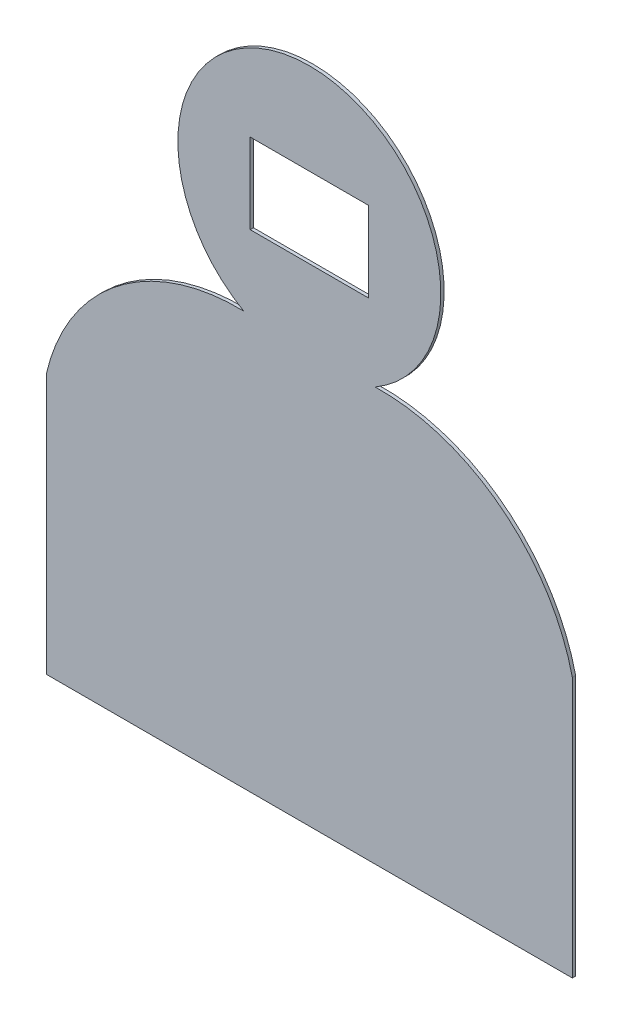
SolidWorks part; units mm, degrees
ref_plane "Front Plane" through (0, 0, 0) normal (0, 0, 1) x (1, 0, 0)
ref_plane "Top Plane" through (0, 0, 0) normal (0, 1, 0) x (1, 0, 0)
ref_plane "Right Plane" through (0, 0, 0) normal (1, 0, 0) x (0, 0, -1)
sketch "Sketch1" plane through (0, 0, 0) normal (0, 0, 1) x (1, 0, 0)
  line L2 (-447.5916, 337.0425) -> (-447.5916, -59.0825)
  line L4 (352.4084, 337.0425) -> (352.4084, -59.0825)
  line L5 (352.4084, -59.0825) -> (-447.5916, -59.0825)
  line L19 (-47.5916, 803.7051) -> (-47.5916, 681.7051)
  line L25 (-47.5916, 681.7051) -> (-47.5916, 803.7051) construction
  line L29 (-137.5916, 803.7051) -> (42.4084, 803.7051)
  line L30 (-137.5916, 803.7051) -> (-137.5916, 681.7051)
  line L31 (-137.5916, 681.7051) -> (42.4084, 681.7051)
  line L32 (42.4084, 803.7051) -> (42.4084, 681.7051)
  arc A1 (52.4084, 569.5) -> (-147.5916, 569.5) centre (-47.5916, 742.7051) ccw
  arc A2 (-147.5916, 569.5) -> (-447.5916, 337.0425) centre (-155.2711, 269.5983) ccw
  arc A3 (52.4084, 569.5) -> (352.4084, 337.0425) centre (60.0879, 269.5983) cw
  point P0 (0, 0)
  point P1 (-47.5916, 942.7051)
  point P2 (352.4084, -59.0825)
  point P11 (-47.5916, 681.7051)
  dimension "D3" = 800
  dimension "D5" = 400
  dimension "D1" = 300
  dimension "D2" = 300
  dimension "D4" = 1001.7876
  dimension "D6" = 180
  dimension "D7" = 122
  dimension "D8" = 628.5825
extrude "Boss-Extrude1" add sketch "Sketch1" along normal blind 5
